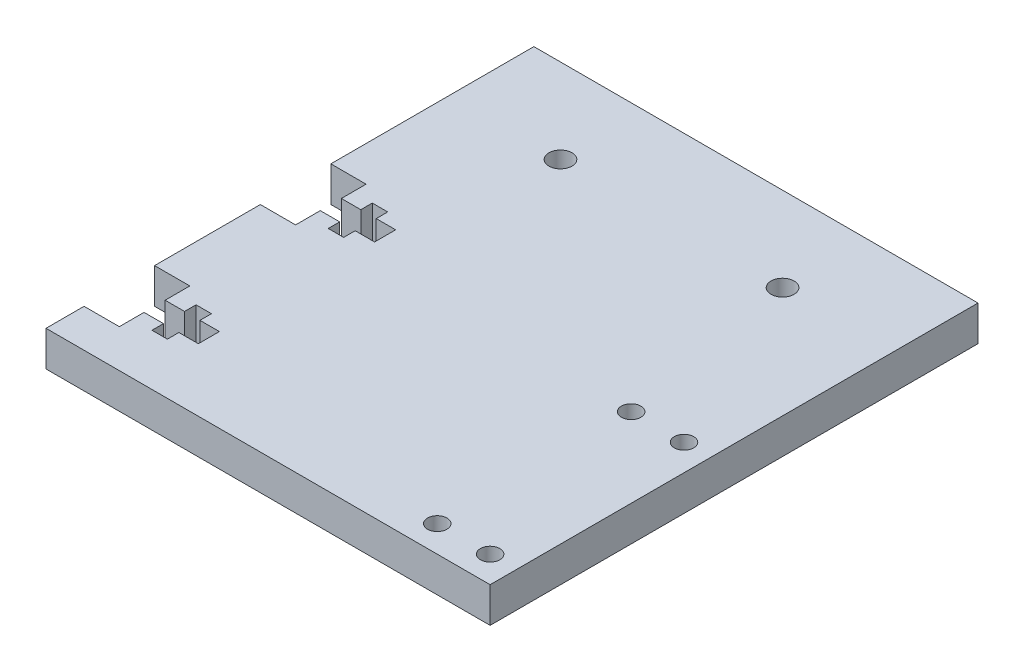
SolidWorks part; units mm, degrees
material "Beech"
ref_plane "Front Plane" through (0, 0, 0) normal (0, 0, 1) x (1, 0, 0)
ref_plane "Top Plane" through (0, 0, 0) normal (0, 1, 0) x (1, 0, 0)
ref_plane "Right Plane" through (0, 0, 0) normal (1, 0, 0) x (0, 0, -1)
sketch "Sketch1" plane through (0, 0, 0) normal (0, 1, 0) x (1, 0, 0)
  line L1 (-40, -43.942) -> (40, -43.942)
  line L2 (-40, -43.942) -> (-40, 43.942)
  line L3 (-40, 43.942) -> (40, 43.942)
  line L4 (40, -43.942) -> (40, 43.942)
  line L5 (-40, -43.942) -> (40, 43.942) construction
  line L6 (-40, 43.942) -> (40, -43.942) construction
  point P0 (0, 0)
  dimension "D1" = 80
  dimension "D2" = 87.884
extrude "Boss-Extrude1" add sketch "Sketch1" along normal mid plane 6.35
hole_wizard "#6 Clearance Hole1" positions "Sketch3" profile "Sketch2" hole size "#6" standard "ANSI Inch" end condition up to next
sketch "Sketch3" plane through (0, 3.175, 0) normal (0, 1, 0) x (1, 0, 0)
  line L0 (40, -43.942) -> (40, 43.942) construction
  line L1 (-40, -43.942) -> (40, -43.942) construction
  point P0 (35.2375, -39.1795)
  dimension "D1" = 4.7625
  dimension "D2" = 4.7625
sketch "Sketch2" plane through (35.2375, 3.175, 39.1795) normal (1, 0, 0) x (0, 0, 1)
  line L0 (0, 0) -> (0, 6.35)
  line L1 (0, 6.35) -> (1.7526, 6.35)
  line L2 (1.7526, 6.35) -> (1.7526, 0)
  line L5 (1.7526, 0) -> (0, 0)
  line L11 (0, -6.35) -> (0, 107.95) construction
  dimension "Thru Hole Dia." = 3.5052
  dimension "Thru Hole Depth" = 6.35
pattern_linear "LPattern1" count 2 spacing 9.525 along (-1, 0, 0) count 2 spacing 34.925 along (0, 0, -1) of "#6 Clearance Hole1"
sketch "Sketch7" plane through (0, 3.175, 0) normal (0, 1, 0) x (1, 0, 0)
  line L0 (-40, 7.366) -> (-40, -5.334)
  line L1 (-40, 7.366) -> (-33.65, 7.366)
  line L2 (-27.3714, 2.9147) -> (-23.871, 2.9147)
  line L3 (-40, -5.334) -> (-33.65, -5.334)
  line L4 (-33.65, -0.8826) -> (-33.65, -5.334)
  line L5 (-30.1496, -0.8826) -> (-33.65, -0.8826)
  line L6 (-23.871, -0.8826) -> (-23.871, 2.9147)
  line L7 (-30.1496, 4.9848) -> (-30.1496, 2.9147)
  line L8 (-27.3714, 4.9848) -> (-30.1496, 4.9848)
  line L9 (-27.3714, 2.9147) -> (-27.3714, 4.9848)
  line L10 (-30.1496, 2.9147) -> (-33.65, 2.9147)
  line L11 (-33.65, 2.9147) -> (-33.65, 7.366)
  line L12 (-27.3714, -0.8826) -> (-27.3714, -2.9527)
  line L13 (-27.3714, -2.9527) -> (-30.1496, -2.9527)
  line L14 (-30.1496, -2.9527) -> (-30.1496, -0.8826)
  line L15 (-27.3714, -0.8826) -> (-23.871, -0.8826)
  line L16 (-23.871, 1.016) -> (-40, 1.016) construction
  line L17 (-40, 43.942) -> (-40, -43.942) construction
  line L18 (-40, -43.942) -> (40, -43.942) construction
  point P18 (-40, 0)
  point P24 (-40.005, 1.016)
  dimension "D1" = 6.35
  dimension "D2" = 1.016
  dimension "D3" = 12.7
  dimension "D4" = 9.779
  dimension "D6" = 38.608
  dimension "D7" = 3.7973
  dimension "D8" = 3.9688
  dimension "D9" = 2.7781
extrude "Cut-Extrude1" cut sketch "Sketch7" against normal up to next
pattern_linear "LPattern3" count 2 spacing 31.75 along (0, 0, 1) of "Cut-Extrude1"
sketch "Sketch10" plane through (0, 3.175, 0) normal (0, 1, 0) x (1, 0, 0)
  line L0 (20, 28.733) -> (-20, 28.733) construction
  line L3 (40, -43.942) -> (40, 43.942) construction
  line L4 (25.7125, -4.2545) -> (25.7125, -39.1795) construction
  circle A0 centre (20, 28.733) radius 2.0828
  circle A1 centre (-20, 28.733) radius 2.0828
  point P8 (25.7125, -21.717)
  dimension "D1" = 40
  dimension "D2" = 4.1656
  dimension "D4" = 20
  dimension "D3" = 50.45
extrude "Cut-Extrude2" cut sketch "Sketch10" against normal through all
